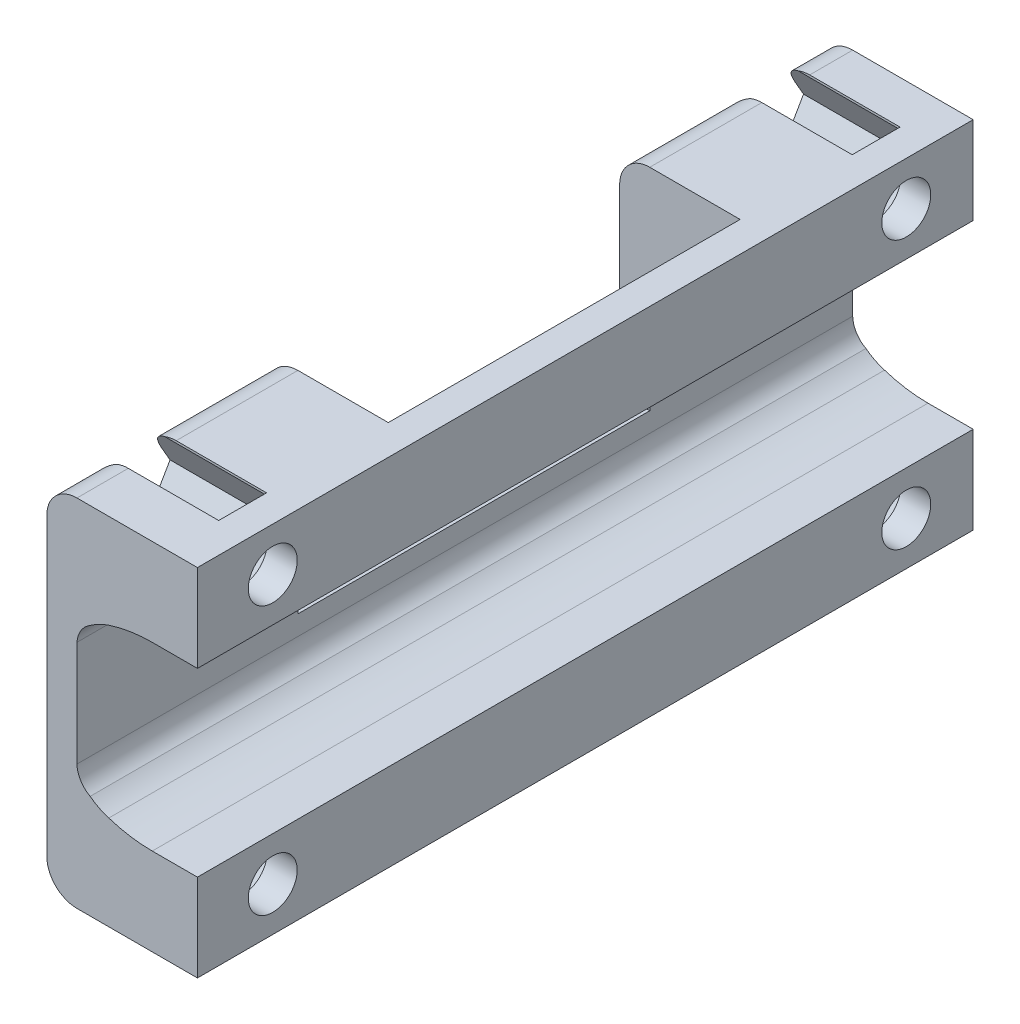
SolidWorks part; units mm, degrees
ref_plane "Alzado" through (0, 0, 0) normal (0, 0, 1) x (1, 0, 0)
ref_plane "Planta" through (0, 0, 0) normal (0, 1, 0) x (1, 0, 0)
ref_plane "Vista lateral" through (0, 0, 0) normal (1, 0, 0) x (0, 0, -1)
sketch "Croquis1" plane through (0, 0, 0) normal (0, 0, 1) x (1, 0, 0)
  line L0 (-16, 14) -> (-13, 14)
  line L1 (-13, 14) -> (-13, 8.2)
  line L2 (-23, 8.2) -> (-13, 8.2)
  line L3 (-23, 31.8) -> (-13, 31.8)
  line L4 (-21, 23.5) -> (-21, 16.5)
  line L5 (-13, 31.8) -> (-13, 26)
  line L6 (-13, 26) -> (-16, 26)
  line L7 (-20, 26) -> (-12, 26) construction
  line L8 (-18.884, 14.4578) -> (-18.884, 25.5422) construction
  line L9 (-20.1232, 15.0859) -> (-20.1232, 24.9141) construction
  line L12 (-23, 8.2) -> (-23, 31.8)
  arc A0 (-16, 14) -> (-18.884, 14.4578) centre (-16, 23.3133) cw
  arc A1 (-18.884, 14.4578) -> (-20.1232, 15.0859) centre (-17.8962, 17.9433) cw
  arc A2 (-20.1232, 15.0859) -> (-21, 16.5) centre (-19.3591, 16.5385) cw
  arc A3 (-18.884, 25.5422) -> (-16, 26) centre (-16, 16.6867) cw
  arc A4 (-18.884, 25.5422) -> (-20.1232, 24.9141) centre (-17.484, 21.2435) ccw
  arc A5 (-20.1232, 24.9141) -> (-21, 23.5) centre (-19.1792, 23.35) ccw
  ellipse E0 centre (-16, 16.5) end of major axis (-21, 16.5) minor radius 2.5 (-21, 16.5) -> (-11, 16.5) ccw construction
  ellipse E1 centre (-16, 23.5) end of major axis (-21, 23.5) minor radius 2.5 (-11, 23.5) -> (-21, 23.5) ccw construction
  dimension "D1" = 2.884
  dimension "D2" = 3.6228
  dimension "D3" = 1.6413
  dimension "D4" = 4.5209
  dimension "D5" = 1.827
  dimension "D6" = 23
extrude "Saliente-Extruir1" add sketch "Croquis1" against normal up to vertex (51.5028 mm away)
sketch "Croquis2" plane through (-23, 0, 0) normal (-1, 0, 0) x (0, 0, 1)
  line L0 (-47.0602, 26) -> (-47.0602, 14) construction
  line L1 (-8.18, 28.9) -> (-6.59, 26.146)
  line L2 (-6.59, 26.146) -> (-3.41, 26.146)
  line L3 (-3.41, 26.146) -> (-1.82, 28.9)
  line L5 (-51.5028, 8.2) -> (0, 8.2) construction
  line L6 (-47.0602, 8.2) -> (-47.0602, 14) construction
  line L12 (0, 31.8) -> (0, 8.2) construction
  line L13 (0, 11.1) -> (-10, 11.1) construction
  line L14 (-1.82, 28.9) -> (-3.41, 31.654)
  line L15 (-1.82, 11.1) -> (-3.41, 13.854)
  line L16 (-3.41, 13.854) -> (-6.59, 13.854)
  line L17 (-6.59, 13.854) -> (-8.18, 11.1)
  line L18 (-8.18, 11.1) -> (-6.59, 8.346)
  line L19 (-6.59, 8.346) -> (-3.41, 8.346)
  line L20 (-3.41, 8.346) -> (-1.82, 11.1)
  line L21 (-47.0602, 26) -> (-47.0602, 31.8) construction
  line L22 (-51.5028, 31.8) -> (0, 31.8) construction
  line L23 (-5, 26) -> (-5, 31.8) construction
  line L24 (-43.8802, 28.9) -> (-45.4702, 31.654)
  line L25 (-45.4702, 31.654) -> (-48.6502, 31.654)
  line L26 (-48.6502, 31.654) -> (-50.2402, 28.9)
  line L27 (-50.2402, 28.9) -> (-48.6502, 26.146)
  line L28 (-48.6502, 26.146) -> (-45.4702, 26.146)
  line L29 (-45.4702, 26.146) -> (-43.8802, 28.9)
  line L30 (-3.41, 31.654) -> (-6.59, 31.654)
  line L31 (-6.59, 31.654) -> (-8.18, 28.9)
  line L32 (-43.8802, 11.1) -> (-45.4702, 13.854)
  line L33 (-45.4702, 13.854) -> (-48.6502, 13.854)
  line L34 (-48.6502, 13.854) -> (-50.2402, 11.1)
  line L35 (-50.2402, 11.1) -> (-48.6502, 8.346)
  line L36 (-48.6502, 8.346) -> (-45.4702, 8.346)
  line L37 (-45.4702, 8.346) -> (-43.8802, 11.1)
  circle A0 centre (-47.0602, 11.1) radius 2.754 construction
  circle A1 centre (-5, 11.1) radius 2.754 construction
  circle A2 centre (-47.0602, 28.9) radius 2.754 construction
  circle A3 centre (-5, 28.9) radius 2.754 construction
  dimension "D3" = 0.146
  dimension "D1" = 5.8
  dimension "D2" = 3.18
  dimension "D4" = 3.18
  dimension "D5" = 2.754
  dimension "D6" = 3.18
extrude "Cortar-Extruir1" cut sketch "Croquis2" against normal blind 8
sketch "Croquis3" plane through (-23, 0, 0) normal (-1, 0, 0) x (0, 0, 1)
  line L5 (-48.6502, 8.346) -> (-48.6502, 8.2)
  line L6 (-51.5028, 8.2) -> (0, 8.2) construction
  line L8 (-51.5028, 31.8) -> (0, 31.8) construction
  line L11 (-45.4702, 8.2) -> (-48.6502, 8.2)
  line L13 (-48.6502, 31.8) -> (-45.4702, 31.8)
  line L14 (-48.6502, 31.8) -> (-48.6502, 31.654)
  line L16 (-45.4702, 31.8) -> (-45.4702, 31.654)
  line L17 (-6.59, 8.346) -> (-6.59, 8.2)
  line L19 (-48.6502, 8.346) -> (-45.4702, 8.346)
  line L22 (-3.41, 8.2) -> (-6.59, 8.2)
  line L24 (-6.59, 31.8) -> (-3.41, 31.8)
  line L25 (-6.59, 31.8) -> (-6.59, 31.654)
  line L27 (-3.41, 31.8) -> (-3.41, 31.654)
  line L29 (-6.59, 8.346) -> (-3.41, 8.346)
  line L30 (-6.59, 31.654) -> (-3.41, 31.654)
  line L31 (-48.6502, 31.654) -> (-45.4702, 31.654)
  line L32 (-3.41, 8.346) -> (-3.41, 8.2)
  line L34 (-45.4702, 8.346) -> (-45.4702, 8.2)
extrude "Cortar-Extruir3" cut sketch "Croquis3" against normal blind 8
sketch "Croquis4" plane through (-23, 0, 0) normal (-1, 0, 0) x (0, 0, 1)
  line L0 (-26.0301, 31.8) -> (-26.0301, 17.8) construction
  line L1 (-45.4702, 31.8) -> (-6.59, 31.8) construction
  line L4 (-26.0301, 31.8) -> (-38.0301, 31.8) construction
  line L5 (-26.0301, 31.8) -> (-14.0301, 31.8) construction
  line L6 (-38.0301, 31.8) -> (-14.6707, 31.8)
  line L7 (-38.0301, 31.8) -> (-38.0301, 17.8)
  line L8 (-38.0301, 17.8) -> (-14.6707, 17.8)
  line L9 (-14.6707, 31.8) -> (-14.6707, 17.8)
  line L10 (-51.5028, 31.8) -> (-48.6502, 31.8) construction
  line L11 (-51.5028, 31.8) -> (-51.5028, 8.2) construction
  dimension "D1" = 13.4727
  dimension "D2" = 36.8321
  dimension "D3" = 14
extrude "Cortar-Extruir4" cut sketch "Croquis4" against normal blind 8
sketch "Croquis5" plane through (0, 0, 0) normal (0, 0, 1) x (1, 0, 0)
  line L0 (-23, 31.8) -> (-21, 31.8)
  line L1 (-21, 16.5) -> (-21, 23.5) construction
  line L2 (-13, 31.8) -> (-23, 31.8) construction
  line L3 (-23, 31.8) -> (-23, 29.8)
  line L4 (-23, 29.8) -> (-21, 29.8) construction
  line L5 (-21, 29.8) -> (-21, 31.8) construction
  line L6 (-23, 8.2) -> (-21, 8.2)
  line L7 (-23, 8.2) -> (-13, 8.2) construction
  line L8 (-23, 8.2) -> (-23, 10.2)
  line L9 (-23, 31.8) -> (-23, 8.2) construction
  line L10 (-21, 8.2) -> (-21, 10.2) construction
  arc A0 (-21, 31.8) -> (-23, 29.8) centre (-21, 29.8) ccw
  arc A1 (-23, 10.2) -> (-21, 8.2) centre (-21, 10.2) ccw
extrude "Cortar-Extruir5" cut sketch "Croquis5" against normal up to vertex
sketch "Croquis6" plane through (-23, 0, 0) normal (-1, 0, 0) x (0, 0, 1)
  line L0 (-26.0301, 10.2) -> (-26.0301, 11.7) construction
  line L1 (-44.3998, 10.2) -> (-7.6604, 10.2) construction
  line L3 (-41.0301, 11.7) -> (-11.0301, 11.7) construction
  text T0 "DAMASHI" font "Century Gothic" height 4.5
extrude "Cortar-Extruir6" cut sketch "Croquis6" against normal blind 1.5
sketch "Croquis7" plane through (-15, 0, 0) normal (-1, 0, 0) x (0, 0, 1)
  line L0 (-6.59, 8.346) -> (-3.41, 8.346) construction
  line L1 (-45.4702, 8.346) -> (-48.6502, 8.346) construction
  line L2 (-47.0602, 8.346) -> (-47.0602, 13.854) construction
  line L3 (-45.4702, 13.854) -> (-48.6502, 13.854) construction
  line L4 (-5, 8.346) -> (-5, 13.854) construction
  line L5 (-3.41, 13.854) -> (-6.59, 13.854) construction
  line L6 (-48.6502, 31.654) -> (-45.4702, 31.654) construction
  line L8 (-6.59, 31.654) -> (-3.41, 31.654) construction
  line L9 (-5, 31.654) -> (-5, 26.146) construction
  line L10 (-6.59, 26.146) -> (-3.41, 26.146) construction
  line L11 (-47.0602, 31.654) -> (-47.0602, 26.146) construction
  line L12 (-48.6502, 26.146) -> (-45.4702, 26.146) construction
  circle A0 centre (-47.0602, 11.1) radius 1.625
  circle A1 centre (-5, 11.1) radius 1.625
  circle A2 centre (-47.0602, 28.9) radius 1.625
  circle A3 centre (-5, 28.9) radius 1.625
  dimension "D1" = 3.25
extrude "Cortar-Extruir7" cut sketch "Croquis7" against normal up to vertex (2 mm away)
